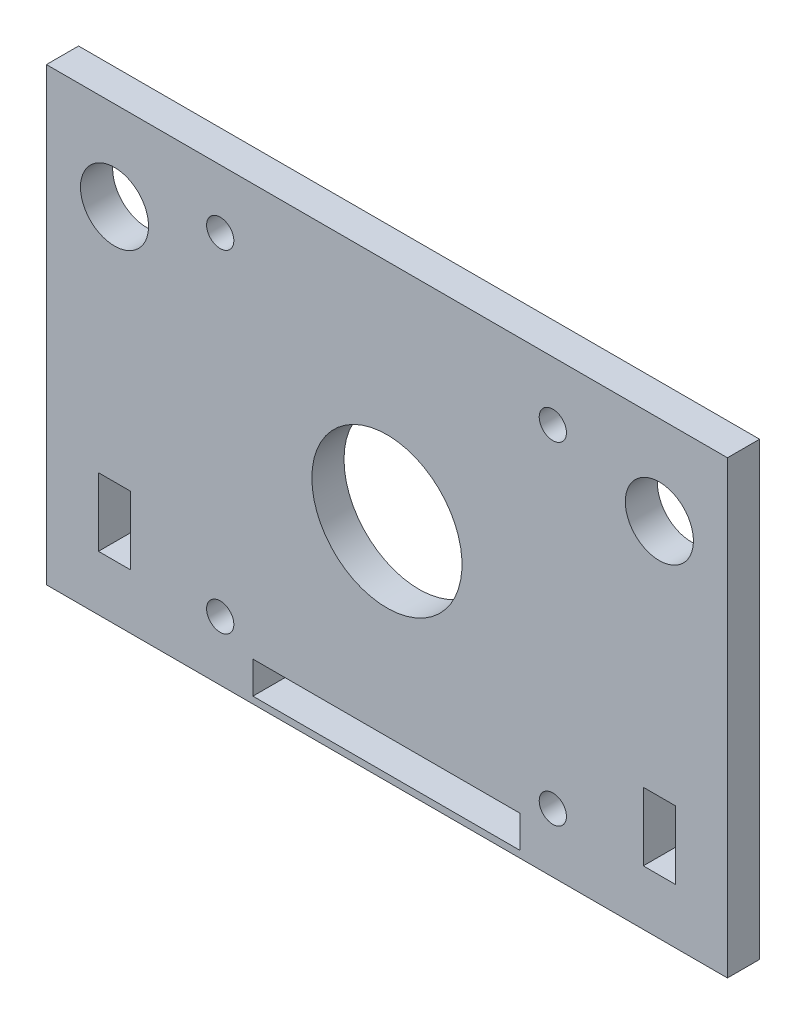
SolidWorks part; units mm, degrees
ref_plane "Front Plane" through (0, 0, 0) normal (0, 0, 1) x (1, 0, 0)
ref_plane "Top Plane" through (0, 0, 0) normal (0, 1, 0) x (1, 0, 0)
ref_plane "Right Plane" through (0, 0, 0) normal (1, 0, 0) x (0, 0, -1)
sketch "Sketch1" plane through (0, 0, 0) normal (0, 0, 1) x (1, 0, 0)
  line L0 (21.0058, 21.005) -> (-21.0058, 21.005) construction
  line L1 (31.75, -21.005) -> (-31.75, -21.005)
  line L2 (31.75, -21.005) -> (31.75, 21.005)
  line L3 (31.75, 21.005) -> (-31.75, 21.005)
  line L4 (-31.75, -21.005) -> (-31.75, 21.005)
  line L5 (-21.0058, -21.005) -> (21.0058, -21.005) construction
  line L6 (-25.4, 9.525) -> (-25.4, -9.525) construction
  line L7 (-12.4968, -17.3728) -> (12.4206, -17.3728)
  line L8 (-12.4968, -17.3728) -> (-12.4968, -20.37)
  line L9 (-12.4968, -20.37) -> (12.4206, -20.37)
  line L10 (12.4206, -17.3728) -> (12.4206, -20.37)
  line L11 (-26.8986, -9.525) -> (-23.9014, -9.525)
  line L12 (-26.8986, -9.525) -> (-26.8986, -15.875)
  line L13 (-26.8986, -15.875) -> (-23.9014, -15.875)
  line L14 (-23.9014, -9.525) -> (-23.9014, -15.875)
  line L15 (23.9014, -9.525) -> (26.8986, -9.525)
  line L16 (23.9014, -9.525) -> (23.9014, -15.875)
  line L17 (23.9014, -15.875) -> (26.8986, -15.875)
  line L18 (26.8986, -9.525) -> (26.8986, -15.875)
  line L19 (25.4, 9.525) -> (25.4, -9.525) construction
  circle A0 centre (-15.5448, -15.4678) radius 1.27 construction
  circle A1 centre (15.4686, -15.4678) radius 1.27 construction
  circle A2 centre (15.4686, 15.5186) radius 1.27 construction
  circle A3 centre (-15.5448, 15.5186) radius 1.27 construction
  circle A4 centre (-15.5448, -15.4678) radius 1.27
  circle A5 centre (15.4686, -15.4678) radius 1.27
  circle A6 centre (15.4686, 15.5186) radius 1.27
  circle A7 centre (-15.5448, 15.5186) radius 1.27
  circle A8 centre (25.4, 12.7) radius 3.175 construction
  circle A9 centre (0, 0) radius 7 construction
  circle A10 centre (-25.4, 12.7) radius 3.175 construction
  circle A11 centre (25.4, 12.7) radius 3.175
  circle A12 centre (0, 0) radius 7
  circle A13 centre (-25.4, 12.7) radius 3.175
  dimension "D1" = 6.35
  dimension "D2" = 6.35
  dimension "D3" = 2.9972
  dimension "D4" = 6.35
  dimension "D5" = 19.05
  dimension "D6" = 2.9972
  dimension "D7" = 3.048
  dimension "D8" = 3.048
  dimension "D9" = 0.635
extrude "Boss-Extrude1" add sketch "Sketch1" along normal blind 2.9972
